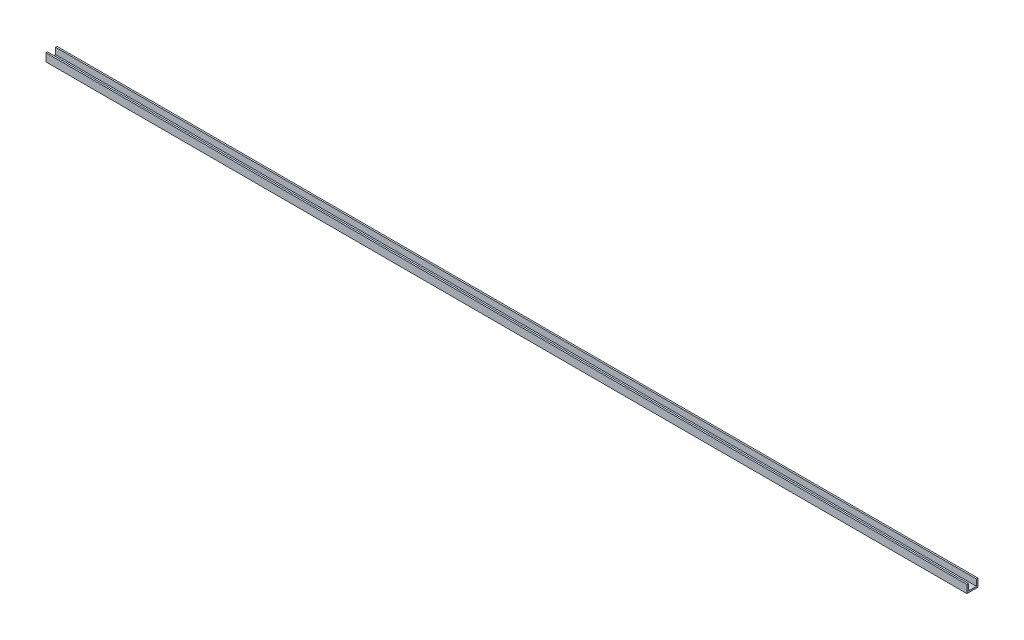
SolidWorks part; units mm, degrees
ref_plane "Front Plane" through (0, 0, 0) normal (0, 0, 1) x (1, 0, 0)
ref_plane "Top Plane" through (0, 0, 0) normal (0, 1, 0) x (1, 0, 0)
ref_plane "Right Plane" through (0, 0, 0) normal (1, 0, 0) x (0, 0, -1)
sketch "Sketch1" plane through (0, 0, 0) normal (1, 0, 0) x (0, 0, -1)
  line L0 (0, 21.5573) -> (0, -20.9315) construction
  line L1 (-36.1687, 0) -> (35.23, 0) construction
  line L2 (-3.5, 0) -> (3.5, 0)
  line L3 (3.5, 0) -> (3.5, 5)
  line L4 (3.5, 5) -> (2.5, 5)
  line L5 (2.5, 5) -> (2.5, 1)
  line L6 (2.5, 1) -> (-2.5, 1)
  line L7 (-2.5, 1) -> (-2.5, 5)
  line L8 (-2.5, 5) -> (-3.5, 5)
  line L9 (-3.5, 5) -> (-3.5, 0)
  dimension "D1" = 7
  dimension "D2" = 1
  dimension "D3" = 1
  dimension "D4" = 5
extrude "Boss-Extrude1" add sketch "Sketch1" along normal blind 580
ref_plane "Plane1" through (580, 5, 2.5) normal (-1, 0, 0) x (0, 0, 1)
